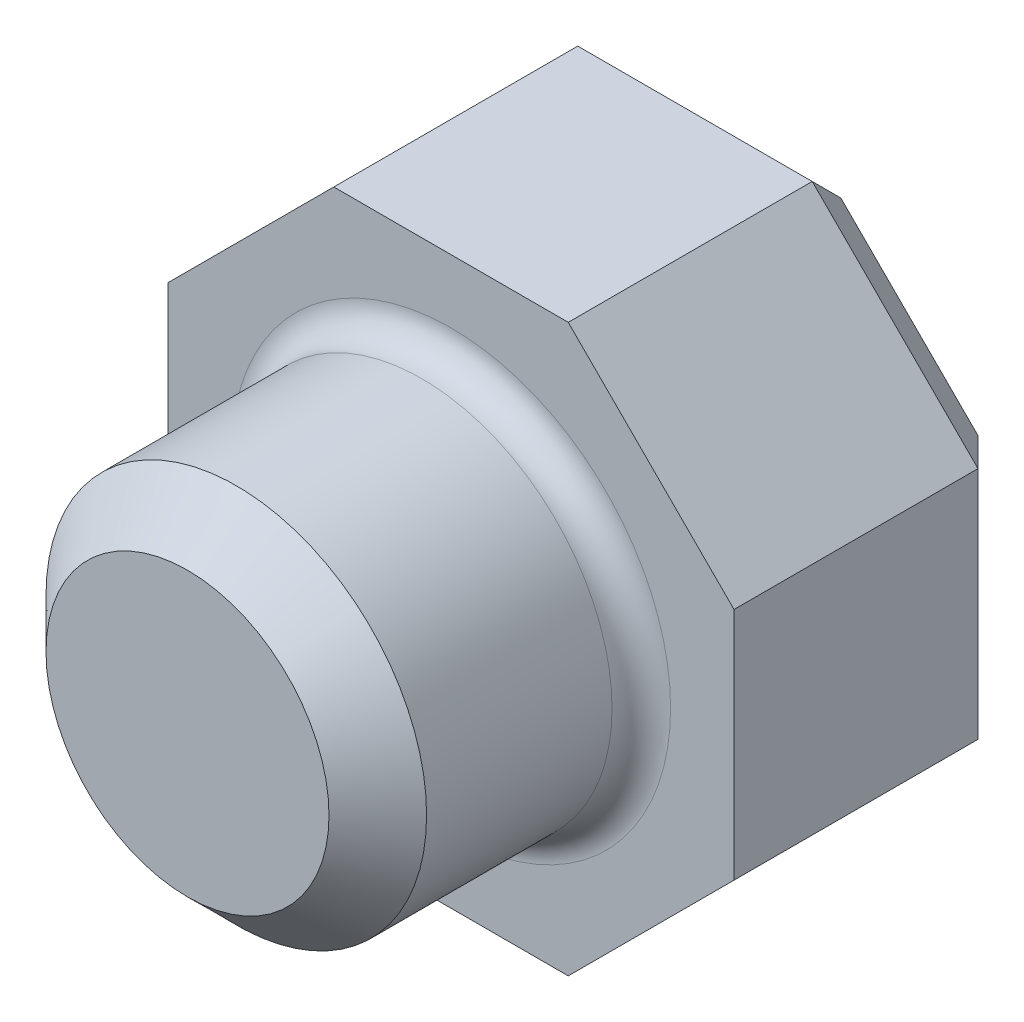
SolidWorks part; units mm, degrees
ref_plane "Alzado" through (0, 0, 0) normal (1, 0, 0) x (0, 1, 0)
ref_plane "Planta" through (0, 0, 0) normal (0, 0, 1) x (0, 1, 0)
ref_plane "Vista lateral" through (0, 0, 0) normal (0, 1, 0) x (-1, 0, 0)
sketch "Croquis1" plane through (0, 0, 0) normal (0, 0, 1) x (0, 1, 0)
  line L0 (0, 0) -> (3.7723, 0) construction
  line L1 (5.8, -2.4024) -> (5.8, 2.4024)
  line L2 (5.8, 2.4024) -> (2.4024, 5.8)
  line L3 (2.4024, 5.8) -> (-2.4024, 5.8)
  line L4 (-2.4024, 5.8) -> (-5.8, 2.4024)
  line L5 (-5.8, 2.4024) -> (-5.8, -2.4024)
  line L6 (-5.8, -2.4024) -> (-2.4024, -5.8)
  line L7 (-2.4024, -5.8) -> (2.4024, -5.8)
  line L8 (2.4024, -5.8) -> (5.8, -2.4024)
  circle A0 centre (0, 0) radius 5.8 construction
  dimension "D1" = 11.6
extrude "Saliente-Extruir1" add sketch "Croquis1" along normal blind 6
sketch "Croquis2" plane through (0, 0, 6) normal (0, 0, 1) x (1, 0, 0)
  circle A0 centre (0, 0) radius 3.9
  dimension "D1" = 7.8
extrude "Saliente-Extruir2" add sketch "Croquis2" along normal blind 5.4
chamfer "Chaflán1" distance 1 angle 45 1 edges at (3.9, 0, 11.4)
fillet "Redondeo1" radius 0.6 1 edges at (3.9, 0, 6)
chamfer "Chaflán2" distance 1 angle 45 8 edges at (5.8, 0, 0) (4.1012, -4.1012, 0) (0, -5.8, 0) (-4.1012, -4.1012, 0) (-5.8, 0, 0) (-4.1012, 4.1012, 0) (0, 5.8, 0) (4.1012, 4.1012, 0)
